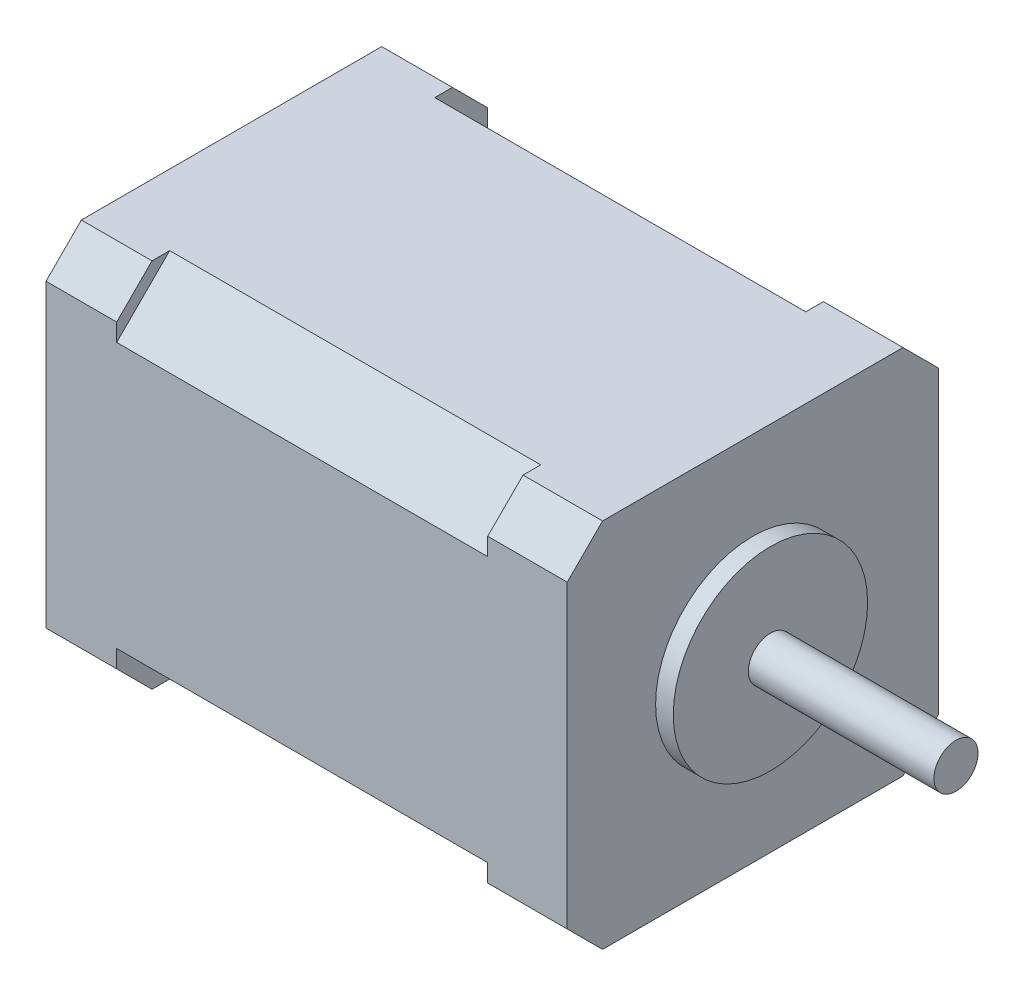
SolidWorks part; units mm, degrees
ref_plane "前视基准面" through (0, 0, 0) normal (0, 0, 1) x (1, 0, 0)
ref_plane "上视基准面" through (0, 0, 0) normal (0, 1, 0) x (1, 0, 0)
ref_plane "右视基准面" through (0, 0, 0) normal (1, 0, 0) x (0, 0, -1)
other "Configuration Table"
sketch "草图1" plane through (0, 0, 0) normal (1, 0, 0) x (0, 0, -1)
  line L1 (-21, 21) -> (21, 21)
  line L2 (-21, 21) -> (-21, -21)
  line L3 (-21, -21) -> (21, -21)
  line L4 (21, 21) -> (21, -21)
  dimension "D1" = 42
  dimension "D2" = 42
  dimension "D3" = 21
  dimension "D4" = 21
extrude "凸台-拉伸1" add sketch "草图1" along normal blind 59
sketch "草图2" plane through (59, 0, 0) normal (1, 0, 0) x (0, 0, -1)
  circle A0 centre (0, 0) radius 11
  dimension "D1" = 22
extrude "凸台-拉伸2" add sketch "草图2" along normal blind 2
sketch "草图3" plane through (61, 0, 0) normal (1, 0, 0) x (0, 0, -1)
  circle A0 centre (0, 0) radius 2.5
  dimension "D1" = 5
extrude "凸台-拉伸3" add sketch "草图3" along normal blind 21
sketch "草图5" plane through (0, 0, 0) normal (-1, 0, 0) x (0, 0, 1)
  line L0 (21, 15) -> (15, 21)
  line L1 (21, 21) -> (21, -21) construction
  line L2 (-21, 21) -> (21, 21) construction
  line L3 (15, 21) -> (21, 21)
  line L4 (21, 21) -> (21, 15)
  line L5 (-0.2819, 0) -> (49999.7181, 0) construction
  line L6 (0, 0) -> (0, -50000) construction
  line L7 (21, -21) -> (21, -15)
  line L8 (15, -21) -> (21, -21)
  line L9 (21, -15) -> (15, -21)
  line L10 (-21, 21) -> (-21, 15)
  line L11 (-15, 21) -> (-21, 21)
  line L12 (-21, 15) -> (-15, 21)
  line L13 (-21, -15) -> (-15, -21)
  line L14 (-15, -21) -> (-21, -21)
  line L15 (-21, -21) -> (-21, -15)
  dimension "D1" = 6
  dimension "D2" = 6
extrude "切除-拉伸1" cut sketch "草图5" against normal blind 42 from offset 8 offset against normal yes
chamfer "倒角1" distance 4 angle 45 8 edges at (4, -21, -21) (54.5, -21, -21) (54.5, -21, 21) (4, -21, 21) (4, 21, 21) (4, 21, -21) (54.5, 21, -21) (54.5, 21, 21)
